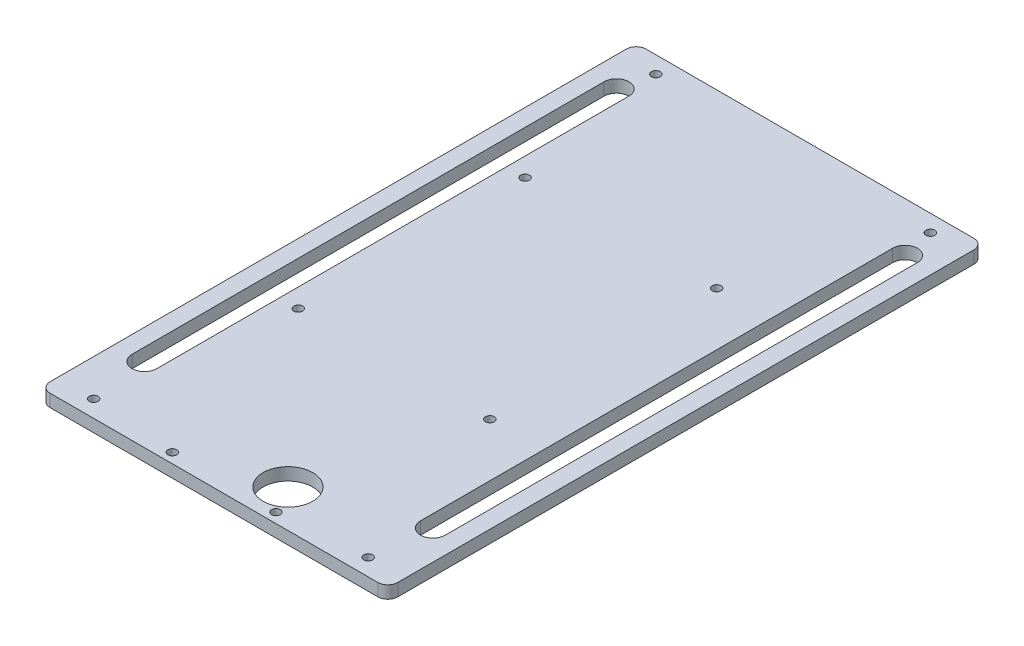
SolidWorks part; units mm, degrees
ref_plane "Front Plane" through (0, 0, 0) normal (0, 0, 1) x (1, 0, 0)
ref_plane "Top Plane" through (0, 0, 0) normal (0, 1, 0) x (1, 0, 0)
ref_plane "Right Plane" through (0, 0, 0) normal (1, 0, 0) x (0, 0, -1)
sketch "Sketch2" plane through (0, 0, 0) normal (0, 0, 1) x (1, 0, 0)
  line L0 (42.8242, -21.393) -> (42.8242, -24.5934)
  line L1 (0, -21.393) -> (0, -24.5934) construction
  line L2 (-46.0758, -24.5934) -> (42.8242, -24.5934)
  line L3 (-46.0758, -21.393) -> (-46.0758, -24.5934)
  line L4 (-46.0758, -21.393) -> (42.8242, -21.393)
  dimension "D1" = 88.9
  dimension "D2" = 3.2004
extrude "Boss-Extrude1" add sketch "Sketch2" along normal blind 152.4 contours L2 L0 L4 L3
sketch "Sketch3" plane through (0, -21.393, 0) normal (0, 1, 0) x (-1, 0, 0)
  line L0 (-42.8242, 149.86) -> (46.0758, 149.86) construction
  line L1 (38.5043, 9.421) -> (38.5043, 0) construction
  line L2 (46.0758, 0) -> (-42.8242, 0) construction
  line L3 (46.0758, 152.4) -> (-42.8242, 152.4) construction
  line L4 (36.73, 148.082) -> (46.0758, 148.082) construction
  line L5 (46.0758, 72.9493) -> (41.6793, 72.9493) construction
  line L6 (35.3293, 12.596) -> (41.6793, 12.596) construction
  line L7 (35.3293, 12.596) -> (35.3293, 133.3026)
  line L8 (35.3293, 133.3026) -> (41.6793, 133.3026) construction
  line L9 (41.6793, 12.596) -> (41.6793, 133.3026)
  line L10 (46.0758, 152.4) -> (-42.8242, 152.4) construction
  line L11 (-11.6838, 149.86) -> (-11.6838, 152.4) construction
  line L12 (-11.6838, 142.748) -> (-11.6838, 149.86) construction
  line L13 (-7.6198, 142.748) -> (-11.6838, 142.748) construction
  line L14 (-42.8242, 152.4) -> (-42.8242, 0) construction
  line L15 (46.0758, 152.4) -> (46.0758, 0) construction
  line L16 (-33.4785, 148.082) -> (-33.4785, 152.4) construction
  line L17 (-33.4785, 148.082) -> (-42.8242, 148.082) construction
  line L18 (36.73, 148.082) -> (36.73, 152.4) construction
  line L19 (-33.4785, 4.318) -> (-42.8242, 4.318) construction
  line L20 (-33.4785, 4.318) -> (-33.4785, 0) construction
  line L21 (46.0758, 0) -> (-42.8242, 0) construction
  line L22 (36.73, 4.318) -> (36.73, 0) construction
  line L23 (36.73, 4.318) -> (46.0758, 4.318) construction
  line L24 (-18.451, 43.9493) -> (-18.451, 0) construction
  line L25 (-42.8242, 43.9493) -> (-18.451, 43.9493) construction
  line L26 (-18.451, 43.9493) -> (30.549, 43.9493) construction
  line L27 (-18.451, 43.9493) -> (-18.451, 101.9493) construction
  line L28 (30.549, 43.9493) -> (30.549, 101.9493) construction
  line L29 (-18.451, 101.9493) -> (30.549, 101.9493) construction
  line L30 (-38.4277, 72.9493) -> (-42.8242, 72.9493) construction
  line L31 (41.6793, 72.9493) -> (-38.4277, 72.9493) construction
  line L46 (-32.0777, 12.596) -> (-38.4277, 12.596) construction
  line L47 (-32.0777, 12.596) -> (-32.0777, 133.3026)
  line L48 (-32.0777, 133.3026) -> (-38.4277, 133.3026) construction
  line L49 (-38.4277, 12.596) -> (-38.4277, 133.3026)
  circle A0 centre (14.8338, 149.86) radius 1.1303
  arc A1 (35.3293, 133.3026) -> (41.6793, 133.3026) centre (38.5043, 133.3026) cw
  arc A2 (41.6793, 12.596) -> (35.3293, 12.596) centre (38.5043, 12.596) cw
  circle A3 centre (-11.6838, 149.86) radius 1.1303
  circle A4 centre (-7.6198, 142.748) radius 6.35
  circle A5 centre (-33.4785, 148.082) radius 1.1303
  circle A6 centre (36.73, 148.082) radius 1.1303
  circle A7 centre (-33.4785, 4.318) radius 1.1303
  circle A8 centre (36.73, 4.318) radius 1.1303
  circle A9 centre (-18.451, 43.9493) radius 1.1303
  circle A10 centre (-18.451, 101.9493) radius 1.1303
  circle A11 centre (30.549, 101.9493) radius 1.1303
  circle A12 centre (30.549, 43.9493) radius 1.1303
  arc A24 (-32.0777, 12.596) -> (-38.4277, 12.596) centre (-35.2527, 12.596) cw
  arc A25 (-38.4277, 133.3026) -> (-32.0777, 133.3026) centre (-35.2527, 133.3026) cw
  point P9 (30.549, 72.9493)
  point P12 (1.6258, 149.86)
  dimension "D5" = 2.2606
  dimension "D9" = 12.7
  dimension "D13" = 2.2606
  dimension "D15" = 9.3458
  dimension "D2" = 4.3965
  dimension "D3" = 120.7066
  dimension "D4" = 6.35
  dimension "D6" = 2.54
  dimension "D7" = 26.5176
  dimension "D8" = 13.208
  dimension "D10" = 7.112
  dimension "D11" = 4.064
  dimension "D12" = 9.421
  dimension "D14" = 4.318
  dimension "D16" = 24.3732
  dimension "D18" = 49
  dimension "D19" = 58
extrude "Cut-Extrude1" cut sketch "Sketch3" against normal through all
sketch "Sketch4" plane through (0, 0, 0) normal (0, 0, -1) x (-1, 0, 0)
  line L0 (1.6258, -21.393) -> (1.6258, -24.5934) construction
  line L1 (46.0758, -21.393) -> (-42.8242, -21.393) construction
  line L2 (46.0758, -24.5934) -> (-42.8242, -24.5934) construction
sketch "Sketch5" plane through (42.8242, 0, 0) normal (1, 0, 0) x (0, 0, -1)
  line L0 (-76.2, -21.393) -> (-76.2, -24.5934) construction
  line L1 (-152.4, -21.393) -> (0, -21.393) construction
  line L2 (-152.4, -24.5934) -> (0, -24.5934) construction
fillet "Fillet2" radius 2.54 4 edges at (42.8242, -22.9932, 152.4) (-46.0758, -22.9932, 152.4) (-46.0758, -22.9932, 0) (42.8242, -22.9932, 0)
